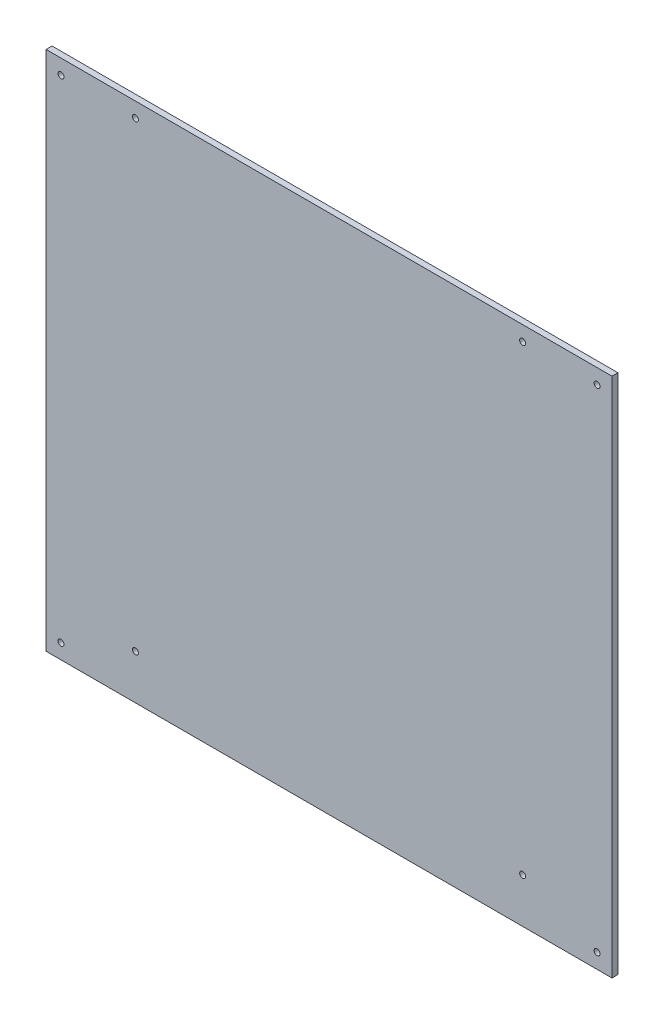
SolidWorks part; units mm, degrees
material "Sklo"
ref_plane "Přední rovina" through (0, 0, 0) normal (0, 0, 1) x (1, 0, 0)
ref_plane "Horní rovina" through (0, 0, 0) normal (0, 1, 0) x (1, 0, 0)
ref_plane "Pravá rovina" through (0, 0, 0) normal (1, 0, 0) x (0, 0, -1)
sketch "Skica1" plane through (0, 0, 0) normal (0, 0, 1) x (1, 0, 0)
  line L1 (190, -175) -> (-190, -175)
  line L2 (190, -175) -> (190, 175)
  line L3 (190, 175) -> (-190, 175)
  line L4 (-190, -175) -> (-190, 175)
  line L5 (190, -175) -> (-190, 175) construction
  line L6 (190, 175) -> (-190, -175) construction
  circle A0 centre (-180, 165) radius 2
  circle A1 centre (180, 165) radius 2
  circle A3 centre (180, -165) radius 2
  circle A5 centre (-180, -165) radius 2
  circle A6 centre (-130, 165) radius 2
  circle A7 centre (130, 165) radius 2
  circle A8 centre (130, -145) radius 2
  circle A9 centre (-130, -145) radius 2
  point P0 (0, 0)
  point P22 (0, 0)
  dimension "D3" = 4
  dimension "D1" = 380
  dimension "D2" = 350
  dimension "D4" = 10
  dimension "D5" = 10
  dimension "D6" = 10
  dimension "D7" = 10
  dimension "D8" = 50
  dimension "D9" = 30
  dimension "D10" = 50
  dimension "D11" = 50
  dimension "D12" = 50
  dimension "D13" = 30
extrude "Přidat vysunutím1" add sketch "Skica1" along normal blind 4
